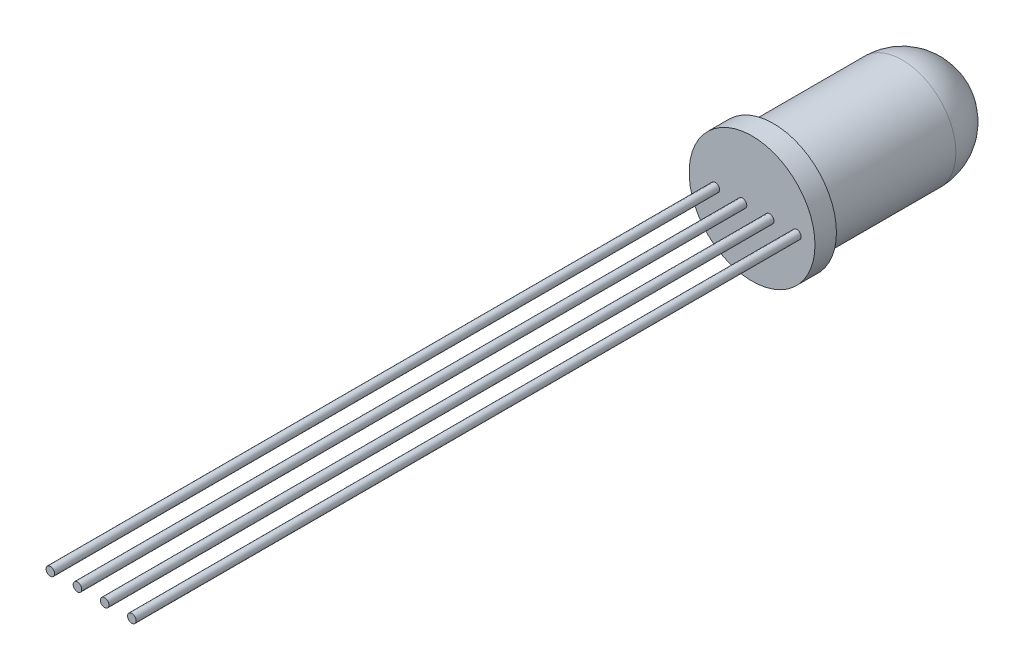
SolidWorks part; units mm, degrees
ref_plane "Front Plane" through (0, 0, 0) normal (0, 0, 1) x (1, 0, 0)
ref_plane "Top Plane" through (0, 0, 0) normal (0, 1, 0) x (1, 0, 0)
ref_plane "Right Plane" through (0, 0, 0) normal (1, 0, 0) x (0, 0, -1)
sketch "Sketch1" plane through (0, 0, 0) normal (0, 0, 1) x (1, 0, 0)
  circle A0 centre (0, 0) radius 2.5
  dimension "D1" = 5
extrude "Boss-Extrude1" add sketch "Sketch1" along normal blind 8.5
sketch "Sketch3" plane through (0, 0, 8.5) normal (0, 0, 1) x (1, 0, 0)
  circle A0 centre (0, 0) radius 2.933
extrude "Boss-Extrude3" add sketch "Sketch3" along normal blind 1
fillet "Fillet1" radius 2.5 1 edges at (2.5, 0, 0)
sketch "Sketch4" plane through (0, 0, 9.5) normal (0, 0, 1) x (1, 0, 0)
  circle A0 centre (-1.7135, 0) radius 0.2
  circle A1 centre (-0.4469, 0) radius 0.2
  circle A2 centre (0.8198, 0) radius 0.2
  circle A3 centre (2.0865, 0) radius 0.2
  point P8 (0, 0)
  dimension "D1" = 0.4
  dimension "D2" = 1.2666
  dimension "D3" = 1.2667
  dimension "D4" = 1.2667
extrude "Boss-Extrude4" add sketch "Sketch4" along normal blind 31
